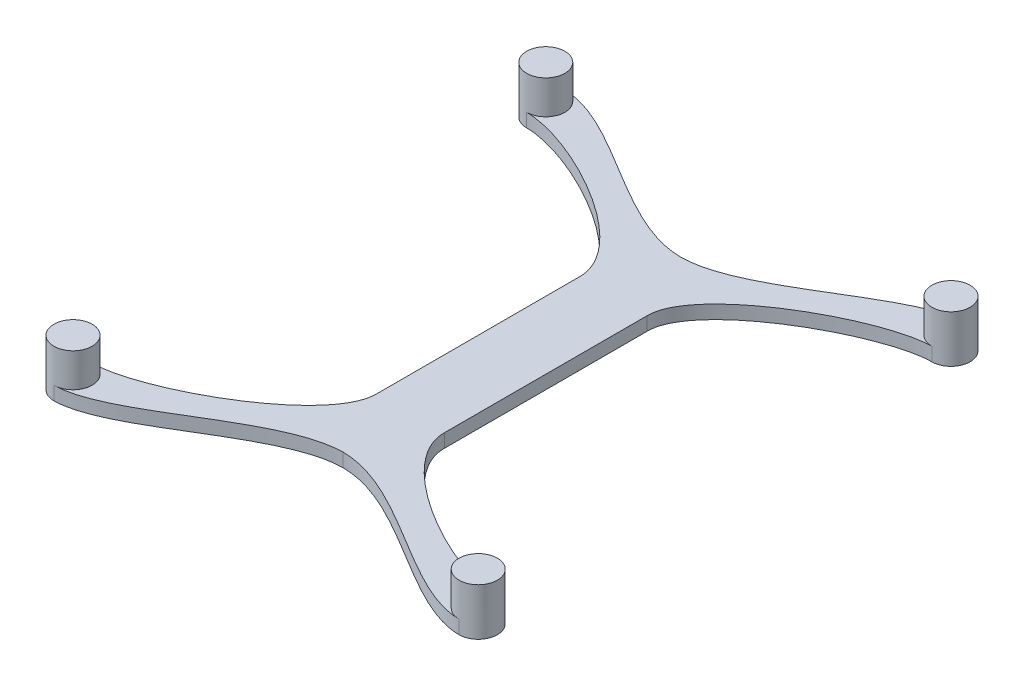
SolidWorks part; units mm, degrees
ref_plane "Front Plane" through (0, 0, 0) normal (0, 0, 1) x (1, 0, 0)
ref_plane "Top Plane" through (0, 0, 0) normal (0, 1, 0) x (1, 0, 0)
ref_plane "Right Plane" through (0, 0, 0) normal (1, 0, 0) x (0, 0, -1)
sketch "Sketch1" plane through (0, 0, 0) normal (0, 1, 0) x (1, 0, 0)
  line L0 (0, 0) -> (-6.35, 0)
  line L1 (-6.35, 0) -> (-6.35, 19.05)
  line L3 (0, 0) -> (0, 31.75)
  circle A0 centre (-38.1, 44.45) radius 3.5941
  spline S0 degree 3 poles (0, 31.75) (-11.9435, 31.8274) (-27.7064, 47.9601) (-38.1, 48.0441) knots 0 0 0 0 1 1 1 1
  spline S1 degree 3 poles (-6.35, 19.05) (-6.1753, 28.394) (-28.7527, 40.7931) (-38.1, 40.8559) knots 0 0 0 0 1 1 1 1
  point P9 (-38.1, 48.0441)
  dimension "D1" = 7.1882
  dimension "D2" = 6.35
  dimension "D3" = 44.45
  dimension "D4" = 38.1
  dimension "D5" = 19.05
  dimension "D6" = 12.7
extrude "Boss-Extrude1" add sketch "Sketch1" along normal blind 2.54 contours S1 L1 L0 L3 S0 A0 | A0 S0
sketch "Sketch2" plane through (0, 2.54, 0) normal (0, 1, 0) x (1, 0, 0)
  circle A0 centre (-38.1, 44.45) radius 3.5941
extrude "Boss-Extrude2" add sketch "Sketch2" along normal blind 6.35
mirror "Mirror1" about plane through (0, 0, 0) normal (1, 0, 0) of "Boss-Extrude1", "Boss-Extrude2"
